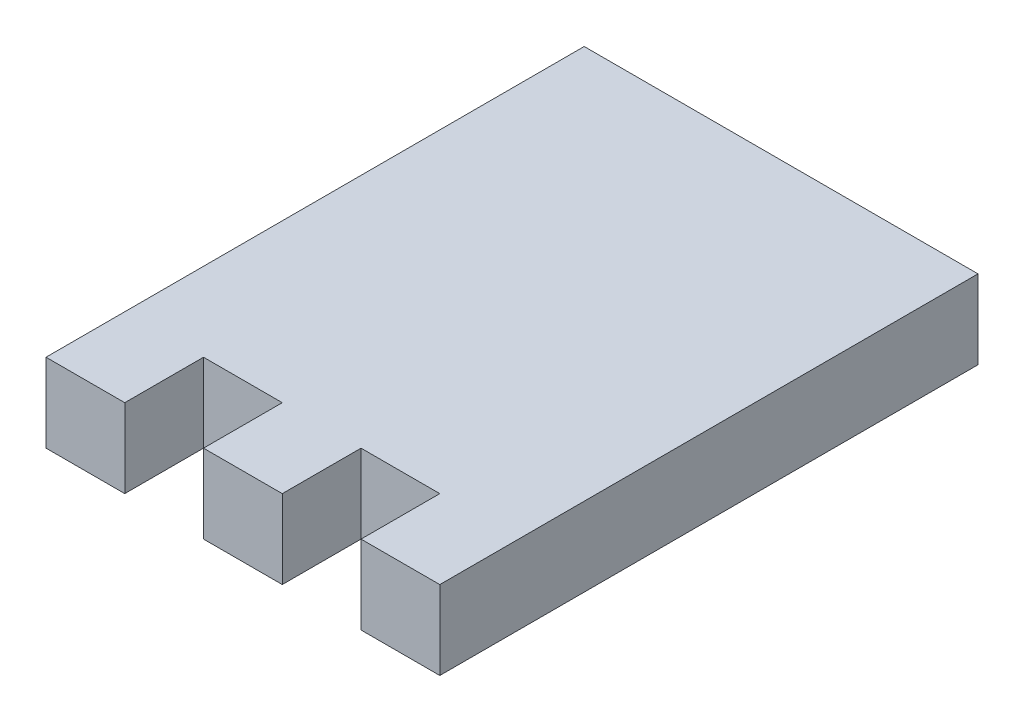
SolidWorks part; units mm, degrees
ref_plane "Front Plane" through (0, 0, 0) normal (0, 0, 1) x (1, 0, 0)
ref_plane "Top Plane" through (0, 0, 0) normal (0, 1, 0) x (1, 0, 0)
ref_plane "Right Plane" through (0, 0, 0) normal (1, 0, 0) x (0, 0, -1)
sketch "Sketch1" plane through (0, 0, 0) normal (0, 1, 0) x (1, 0, 0)
  line L0 (0.019, 12.8725) -> (0.019, -7.6275) construction
  line L1 (-7.481, -7.6275) -> (-4.481, -7.6275)
  line L2 (-7.481, -7.6275) -> (-7.481, 12.8725)
  line L3 (-7.481, 12.8725) -> (7.519, 12.8725)
  line L4 (7.519, -7.6275) -> (7.519, 12.8725)
  line L5 (-7.481, -7.6275) -> (7.519, 12.8725) construction
  line L6 (-7.481, 12.8725) -> (7.519, -7.6275) construction
  line L7 (-4.481, -7.6275) -> (-4.481, -4.6275)
  line L8 (-4.481, -4.6275) -> (-1.481, -4.6275)
  line L9 (-1.481, -7.6275) -> (-1.481, -4.6275)
  line L10 (4.519, -4.6275) -> (1.519, -4.6275)
  line L11 (1.519, -7.6275) -> (1.519, -4.6275)
  line L12 (4.519, -7.6275) -> (4.519, -4.6275)
  line L13 (-1.481, -7.6275) -> (1.519, -7.6275)
  line L14 (4.519, -7.6275) -> (7.519, -7.6275)
  point P0 (0.019, 2.6225)
  dimension "D1" = 20.5
  dimension "D2" = 3
  dimension "D3" = 3
  dimension "D4" = 1.5
  dimension "D5" = 3
  dimension "D6" = 3
  dimension "D7" = 3
extrude "Boss-Extrude1" add sketch "Sketch1" along normal blind 3 contours L2 L3 L4 L14 L12 L10 L11 L13 L9 L8 L7 L1
